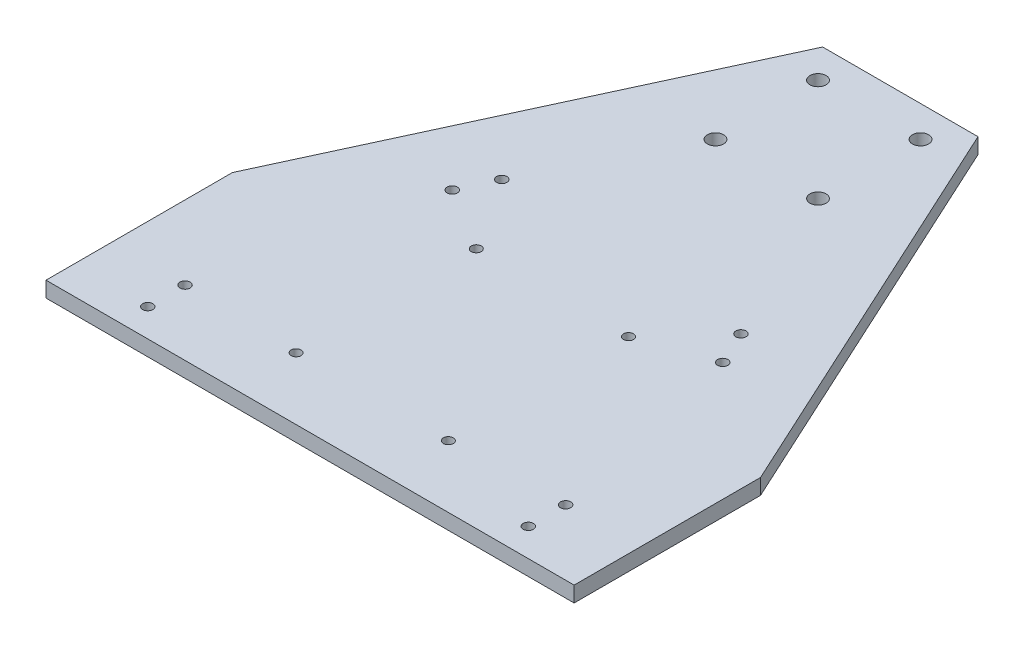
SolidWorks part; units mm, degrees
ref_plane "Front" through (0, 0, 0) normal (0, 0, 1) x (1, 0, 0)
ref_plane "Top" through (0, 0, 0) normal (0, 1, 0) x (1, 0, 0)
ref_plane "Right" through (0, 0, 0) normal (1, 0, 0) x (0, 0, -1)
sketch "Эскиз1" plane through (0, 0, 0) normal (0, 1, 0) x (1, 0, 0)
  line L0 (85, 60) -> (85, 190) construction
  line L1 (0, 0) -> (170, 0)
  line L2 (0, 0) -> (0, 60)
  line L3 (0, 60) -> (170, 60) construction
  line L4 (170, 0) -> (170, 60)
  line L5 (0, 0) -> (170, 60) construction
  line L6 (0, 60) -> (170, 0) construction
  line L7 (110, 190) -> (60, 190)
  line L8 (0, 60) -> (60, 190)
  line L9 (110, 190) -> (170, 60)
  point P4 (85, 30)
  point P11 (85, 190)
extrude "Бобышка-Вытянуть1" add sketch "Эскиз1" along normal blind 5
sketch "Эскиз2" plane through (0, 5, 0) normal (0, 1, 0) x (1, 0, 0)
  line L0 (85, 0) -> (85, 20) construction
  line L2 (85, 20) -> (60.5, 20) construction
  line L3 (0, 0) -> (170, 0) construction
  circle A0 centre (60.5, 20) radius 1.6
extrude "Вырез-Вытянуть1" cut sketch "Эскиз2" against normal blind 5
pattern_linear "Линейный массив1" count 2 spacing 58 along (0, 0, -1) count 2 spacing 49 along (1, 0, 0) of "Вырез-Вытянуть1"
sketch "Эскиз3" plane through (0, 5, 0) normal (0, 1, 0) x (1, 0, 0)
  line L0 (85, 190) -> (85, 180) construction
  line L1 (110, 190) -> (60, 190) construction
  line L2 (85, 180) -> (101.5, 180) construction
  circle A0 centre (101.5, 180) radius 2.6
extrude "Вырез-Вытянуть2" cut sketch "Эскиз3" against normal blind 10
pattern_linear "Линейный массив2" count 2 spacing 33 along (-1, 0, 0) count 2 spacing 33 along (0, 0, 1) of "Вырез-Вытянуть2"
sketch "Эскиз4" plane through (0, 5, 0) normal (0, 1, 0) x (1, 0, 0)
  circle A0 centre (23.75, 8.9997) radius 1.65 construction
  circle A1 centre (23.75, 20.9997) radius 1.65 construction
  circle A2 centre (146.25, 20.9997) radius 1.65 construction
  circle A3 centre (146.25, 8.9997) radius 1.65 construction
  circle A4 centre (45.2743, 101.4196) radius 1.65 construction
  circle A5 centre (40.2456, 90.524) radius 1.65 construction
  circle A6 centre (126.8211, 96.8796) radius 1.65 construction
  circle A7 centre (131.8498, 85.9841) radius 1.65 construction
  circle A8 centre (23.75, 8.9997) radius 1.65
  circle A9 centre (23.75, 20.9997) radius 1.65
  circle A10 centre (146.25, 20.9997) radius 1.65
  circle A11 centre (146.25, 8.9997) radius 1.65
  circle A12 centre (45.2743, 101.4196) radius 1.65
  circle A13 centre (40.2456, 90.524) radius 1.65
  circle A14 centre (126.8211, 96.8796) radius 1.65
  circle A15 centre (131.8498, 85.9841) radius 1.65
extrude "Вырез-Вытянуть4" cut sketch "Эскиз4" against normal blind 10
